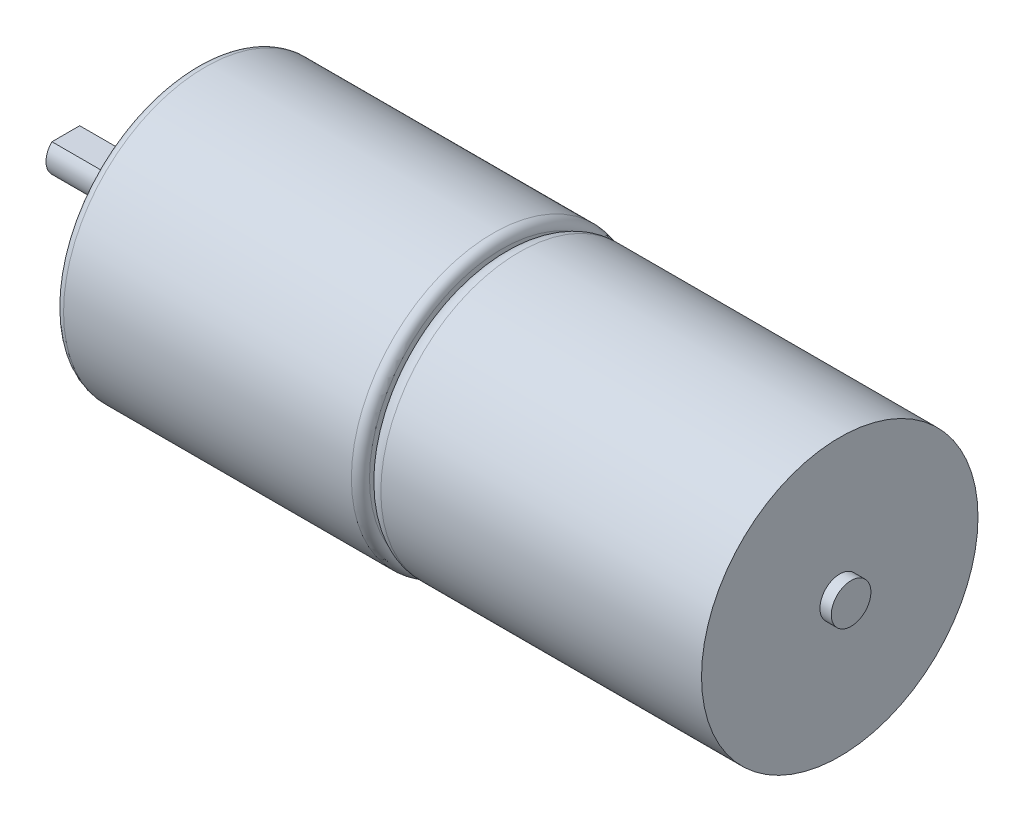
SolidWorks part; units mm, degrees
ref_plane "Alzado" through (0, 0, 0) normal (0, 0, 1) x (1, 0, 0)
ref_plane "Planta" through (0, 0, 0) normal (0, 1, 0) x (1, 0, 0)
ref_plane "Vista lateral" through (0, 0, 0) normal (1, 0, 0) x (0, 0, -1)
sketch "Croquis1" plane through (0, 0, 0) normal (0, 0, 1) x (1, 0, 0)
  line L0 (-226.683, 0) -> (11107.4684, 0) construction
  line L1 (0, 0) -> (0, 1.75)
  line L2 (0, 1.75) -> (-1, 1.75)
  line L3 (-1, 1.75) -> (-1, 12.2)
  line L4 (-1, 12.2) -> (-29.3, 12.2)
  line L5 (-30.8, 10.7) -> (-30.8, 0)
  line L6 (-30.8, 0) -> (0, 0)
  arc A0 (-29.3, 12.2) -> (-30.8, 10.7) centre (-29.3, 10.7) ccw
  dimension "D4" = 1.5
  dimension "D1" = 1.75
  dimension "D2" = 12.2
  dimension "D3" = 30.8
  dimension "D5" = 1
revolve "Revolución1" add sketch "Croquis1" angle 360 about L0
sketch "Croquis2" plane through (0, 0, 0) normal (0, 0, 1) x (1, 0, 0)
  line L0 (-1000, 0) -> (49000, 0) construction
  line L2 (-57, 12.5) -> (-31.6, 12.5)
  line L3 (-30.8, 11.7) -> (-30.8, 0)
  line L4 (-30.8, 0) -> (-69.3, 0)
  line L5 (-30.8, 10.7) -> (-30.8, -10.7) construction
  line L6 (-57.8, 11.7) -> (-57.8, 3.5)
  line L7 (-57.8, 3.5) -> (-60.3, 3.5)
  line L8 (-60.3, 3.5) -> (-60.3, 1.75)
  line L9 (-60.3, 1.75) -> (-69.3, 1.75)
  line L10 (-69.3, 1.75) -> (-69.3, 0)
  arc A0 (-57.8, 11.7) -> (-57, 12.5) centre (-57, 11.7) cw
  arc A1 (-31.6, 12.5) -> (-30.8, 11.7) centre (-31.6, 11.7) cw
  dimension "D2" = 0.8
  dimension "D3" = 27
  dimension "D1" = 12.5
  dimension "D4" = 2.5
  dimension "D5" = 11.5
  dimension "D6" = 1.75
  dimension "D7" = 3.5
revolve "Revolución2" add sketch "Croquis2" angle 360 about L0
sketch "Croquis3" plane through (-69.3, 0, 0) normal (-1, 0, 0) x (0, 0, 1)
  line L1 (-1.2247, 2.25) -> (1.2247, 2.25)
  line L2 (-1.2247, 2.25) -> (-1.2247, 1.25)
  line L3 (-1.2247, 1.25) -> (1.2247, 1.25)
  line L4 (1.2247, 2.25) -> (1.2247, 1.25)
  line L5 (-1.2247, 2.25) -> (1.2247, 1.25) construction
  line L6 (-1.2247, 1.25) -> (1.2247, 2.25) construction
  circle A0 centre (0, 0) radius 1.75 construction
  circle A1 centre (0, 0) radius 1.75 construction
  point P0 (0, 1.75)
  dimension "D1" = 1
extrude "Cortar-Extruir1" cut sketch "Croquis3" against normal blind 5
sketch "Croquis4" plane through (-57.8, 0, 0) normal (-1, 0, 0) x (0, 0, 1)
  line L0 (-1000, 0) -> (49000, 0) construction
  circle A0 centre (-8.5, 0) radius 1.5
  circle A1 centre (8.5, 0) radius 1.5
  dimension "D1" = 3
  dimension "D2" = 17
  dimension "D3" = 8.5
extrude "Cortar-Extruir2" cut sketch "Croquis4" against normal blind 2
sketch "Croquis6" plane through (-57.8, 0, 0) normal (-1, 0, 0) x (0, 0, 1)
  line L0 (-1000, 0) -> (49000, 0) construction
  line L1 (0, -1000) -> (0, 49000) construction
  circle A0 centre (0, 8) radius 2.6
  circle A1 centre (0, -8) radius 2.6
  dimension "D1" = 5.2
  dimension "D2" = 8
extrude "Cortar-Extruir3" cut sketch "Croquis6" against normal blind 0.7
sketch "Croquis7" plane through (-57.1, 0, 0) normal (-1, 0, 0) x (0, 0, 1)
  line L0 (0, 10.6) -> (0, 5.4) construction
  line L1 (2.6, 8) -> (-2.6, 8) construction
  line L2 (0.2, 9.9) -> (-0.2, 9.9)
  line L3 (-0.2, 9.9) -> (-0.2, 8.2)
  line L4 (-0.2, 8.2) -> (-1.9, 8.2)
  line L5 (-1.9, 8.2) -> (-1.9, 7.8)
  line L6 (1.9, 8.2) -> (1.9, 7.8)
  line L7 (0.2, 8.2) -> (1.9, 8.2)
  line L8 (0.2, 9.9) -> (0.2, 8.2)
  line L9 (0.2, 6.1) -> (0.2, 7.8)
  line L10 (-0.2, 6.1) -> (-0.2, 7.8)
  line L11 (0.2, 7.8) -> (1.9, 7.8)
  line L12 (0.2, 6.1) -> (-0.2, 6.1)
  line L13 (-0.2, 7.8) -> (-1.9, 7.8)
  line L14 (-1000, 0) -> (49000, 0) construction
  line L15 (-0.2, -7.8) -> (-1.9, -7.8)
  line L16 (0.2, -6.1) -> (-0.2, -6.1)
  line L17 (0.2, -7.8) -> (1.9, -7.8)
  line L18 (-0.2, -6.1) -> (-0.2, -7.8)
  line L19 (0.2, -6.1) -> (0.2, -7.8)
  line L20 (0.2, -9.9) -> (0.2, -8.2)
  line L21 (0.2, -8.2) -> (1.9, -8.2)
  line L22 (1.9, -8.2) -> (1.9, -7.8)
  line L23 (-1.9, -8.2) -> (-1.9, -7.8)
  line L24 (-0.2, -8.2) -> (-1.9, -8.2)
  line L25 (-0.2, -9.9) -> (-0.2, -8.2)
  line L26 (0.2, -9.9) -> (-0.2, -9.9)
  circle A0 centre (0, 8) radius 2.6 construction
  circle A1 centre (0, 8) radius 2.6 construction
  point P19 (0, 9.9)
  point P24 (1.9, 8)
  point P25 (-1.9, 8)
  point P40 (-1.9, -8)
  point P41 (1.9, -8)
  point P42 (0, -9.9)
  dimension "D1" = 0.2
  dimension "D2" = 1.7
extrude "Cortar-Extruir4" cut sketch "Croquis7" against normal blind 0.5
